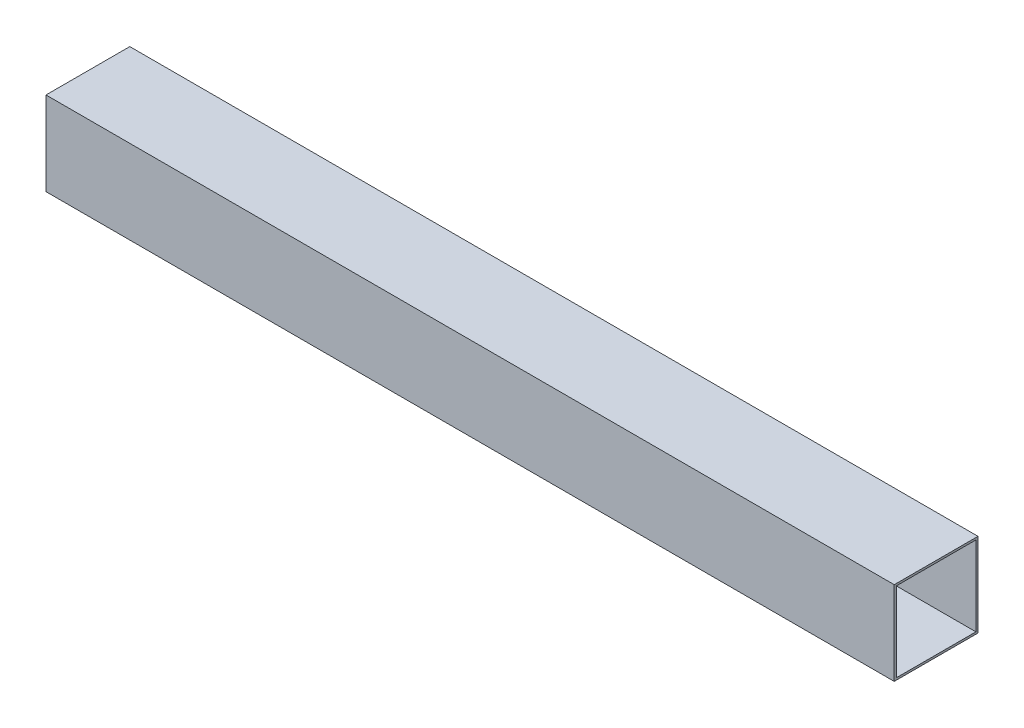
SolidWorks part; units mm, degrees
ref_plane "前视基准面" through (0, 0, 0) normal (0, 0, 1) x (1, 0, 0)
ref_plane "上视基准面" through (0, 0, 0) normal (0, 1, 0) x (1, 0, 0)
ref_plane "右视基准面" through (0, 0, 0) normal (1, 0, 0) x (0, 0, -1)
sketch "草图1" plane through (0, 0, 0) normal (1, 0, 0) x (0, 0, -1)
  line L0 (-38, 38) -> (-38, -38)
  line L1 (-40, 40) -> (40, 40)
  line L2 (-40, 40) -> (-40, -40)
  line L3 (-40, -40) -> (40, -40)
  line L4 (40, 40) -> (40, -40)
  line L5 (-38, -38) -> (38, -38)
  line L6 (38, 38) -> (38, -38)
  line L7 (-38, 38) -> (38, 38)
  point P4 (0, 40)
  point P6 (40, 0)
  dimension "D1" = 80
  dimension "D2" = 2
extrude "凸台-拉伸1" add sketch "草图1" along normal mid plane 810
sketch "草图2" plane through (0, 0, 0) normal (0, 1, 0) x (1, 0, 0)
  line L0 (-410, 410) -> (410, 410)
  line L1 (-407, 407) -> (407, 407)
  line L2 (-407, 407) -> (-407, -407)
  line L3 (-407, -407) -> (407, -407)
  line L4 (407, 407) -> (407, -407)
  line L5 (410, 410) -> (410, -410)
  line L6 (-410, -410) -> (410, -410)
  line L7 (-410, 410) -> (-410, -410)
  point P4 (407, 0)
  point P6 (0, 407)
  dimension "D1" = 814
  dimension "D2" = 3
